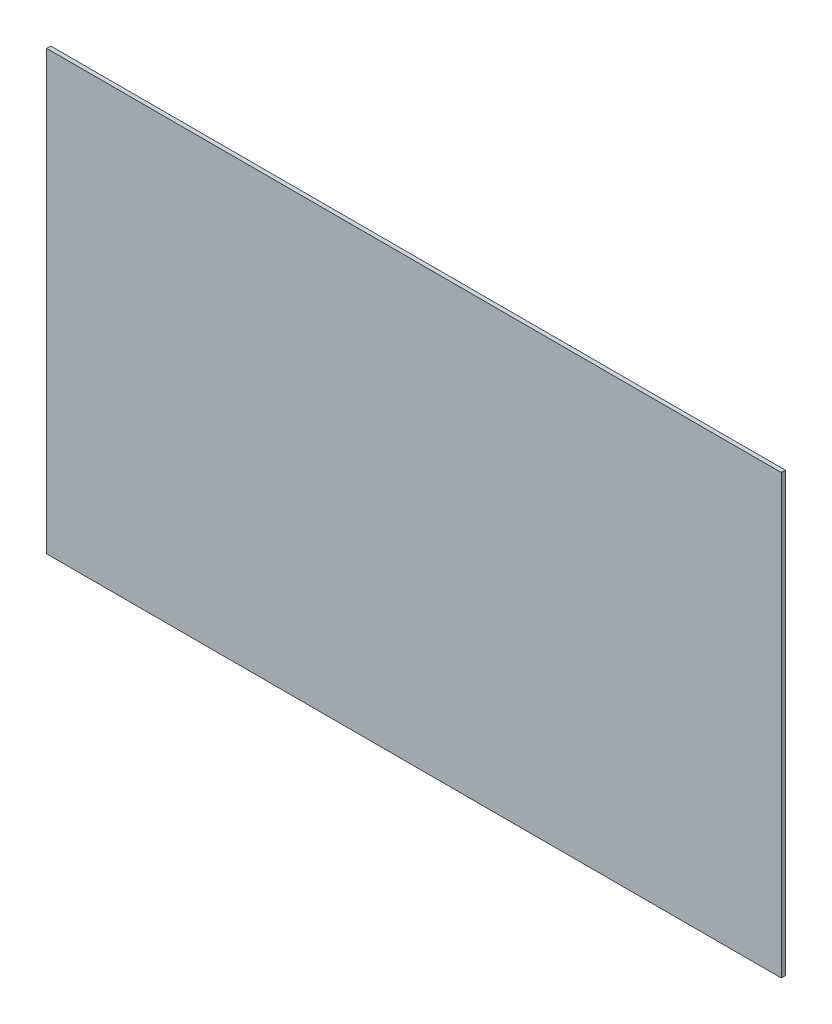
SolidWorks part; units mm, degrees
ref_plane "前视基准面" through (0, 0, 0) normal (0, 0, 1) x (1, 0, 0)
ref_plane "上视基准面" through (0, 0, 0) normal (0, 1, 0) x (1, 0, 0)
ref_plane "右视基准面" through (0, 0, 0) normal (1, 0, 0) x (0, 0, -1)
sketch "草图1" plane through (0, 0, 0) normal (0, 0, 1) x (1, 0, 0)
  line L1 (-268.5, 160) -> (268.5, 160)
  line L2 (-268.5, 160) -> (-268.5, -160)
  line L3 (-268.5, -160) -> (268.5, -160)
  line L4 (268.5, 160) -> (268.5, -160)
  line L5 (-268.5, 160) -> (268.5, -160) construction
  line L6 (-268.5, -160) -> (268.5, 160) construction
  point P0 (0, 0)
extrude "凸台-拉伸1" add sketch "草图1" along normal blind 3
